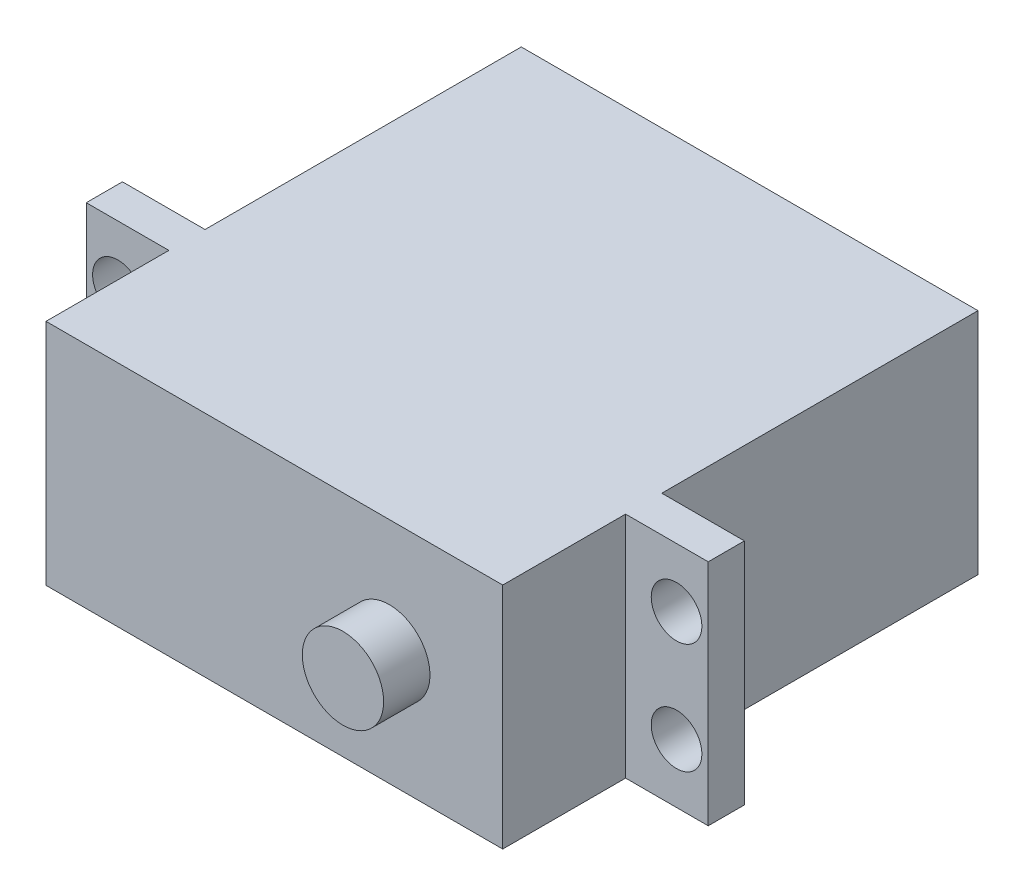
SolidWorks part; units mm, degrees
ref_plane "Front Plane" through (0, 0, 0) normal (0, 0, 1) x (1, 0, 0)
ref_plane "Top Plane" through (0, 0, 0) normal (0, 1, 0) x (1, 0, 0)
ref_plane "Right Plane" through (0, 0, 0) normal (1, 0, 0) x (0, 0, -1)
sketch "Sketch1" plane through (0, 0, 0) normal (0, 0, 1) x (1, 0, 0)
  line L1 (0, 0) -> (40.0812, 0)
  line L2 (0, 0) -> (0, 20.066)
  line L3 (0, 20.066) -> (40.0812, 20.066)
  line L4 (40.0812, 0) -> (40.0812, 20.066)
  dimension "D1" = 20.066
  dimension "D2" = 40.0812
extrude "Boss-Extrude1" add sketch "Sketch1" along normal blind 41.7068
sketch "Sketch2" plane through (40.0812, 0, 0) normal (1, 0, 0) x (0, 0, -1)
  line L0 (-41.7068, 20.066) -> (0, 20.066) construction
  line L1 (-30.9245, 20.066) -> (-27.7495, 20.066)
  line L2 (-30.9245, 20.066) -> (-30.9245, 0)
  line L3 (-30.9245, 0) -> (-27.7495, 0)
  line L4 (-27.7495, 20.066) -> (-27.7495, 0)
  line L5 (-41.7068, 0) -> (0, 0) construction
  line L8 (0, 0) -> (0, 20.066) construction
  dimension "D1" = 30.9245
  dimension "D2" = 3.175
extrude "Boss-Extrude2" add sketch "Sketch2" along normal blind 7.25
ref_plane "Plane1" through (20.0406, 0, 0) normal (-1, 0, 0) x (0, 0, 1)
mirror "Mirror1" about plane through (20.0406, 0, 0) normal (-1, 0, 0) of "Boss-Extrude2"
sketch "Sketch3" plane through (0, 0, 30.9245) normal (0, 0, 1) x (1, 0, 0)
  line L0 (-7.25, 10.033) -> (47.3312, 10.033) construction
  line L1 (-7.25, 20.066) -> (-7.25, 0) construction
  line L2 (47.3312, 20.066) -> (47.3312, 0) construction
  line L3 (20.0406, 0) -> (20.0406, 20.066) construction
  line L5 (40.0812, 20.066) -> (0, 20.066) construction
  circle A0 centre (44.5516, 5.1816) radius 2.2225
  circle A5 centre (-4.4704, 5.1816) radius 2.2225
  circle A6 centre (-4.4704, 14.8844) radius 2.2225
  circle A7 centre (44.5516, 14.8844) radius 2.2225
  point P12 (20.0406, 10.033)
  dimension "D2" = 4.445
  dimension "D1" = 9.7028
  dimension "D3" = 49.022
extrude "Cut-Extrude1" cut sketch "Sketch3" against normal up to next
sketch "Sketch4" plane through (0, 0, 41.7068) normal (0, 0, 1) x (1, 0, 0)
  line L0 (40.0812, 0) -> (40.0812, 20.066) construction
  line L1 (0, 20.066) -> (0, 0) construction
  circle A0 centre (30.1244, 10.033) radius 3.5687
  point P5 (40.0812, 10.033)
  dimension "D2" = 7.1374
  dimension "D1" = 30.1244
extrude "Boss-Extrude3" add sketch "Sketch4" along normal blind 4.064
